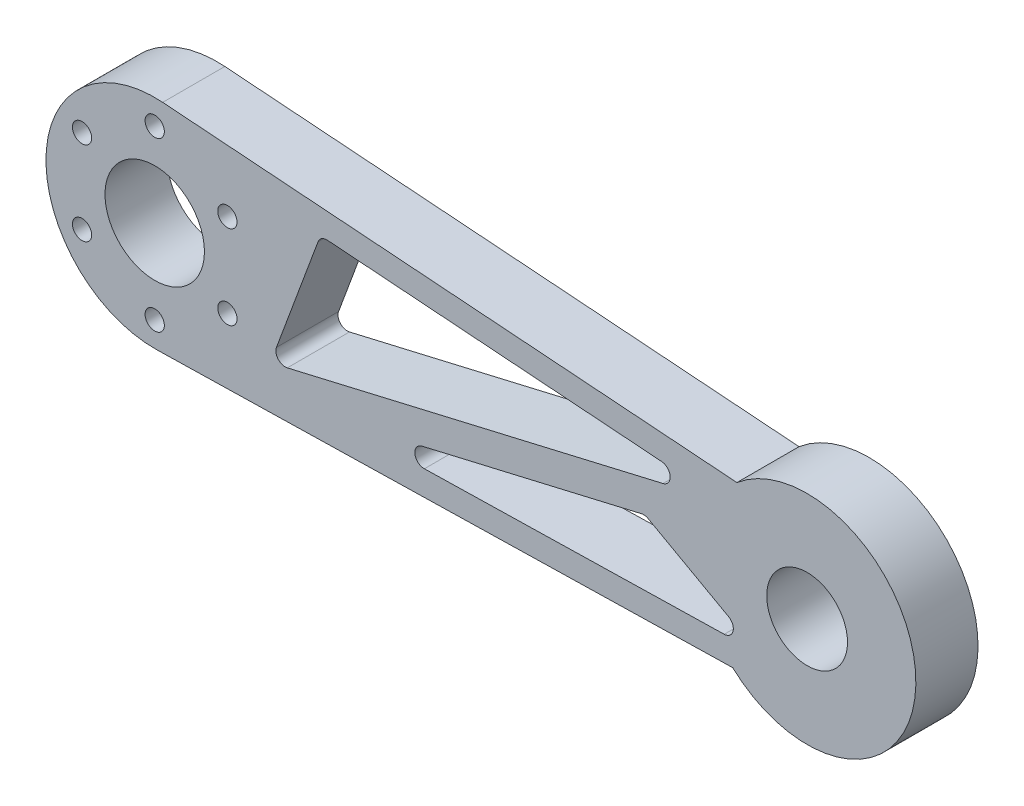
SolidWorks part; units mm, degrees
ref_plane "前视基准面" through (0, 0, 0) normal (0, 0, 1) x (1, 0, 0)
ref_plane "上视基准面" through (0, 0, 0) normal (0, 1, 0) x (1, 0, 0)
ref_plane "右视基准面" through (0, 0, 0) normal (1, 0, 0) x (0, 0, -1)
sketch "草图1" plane through (0, 0, 0) normal (0, 0, 1) x (1, 0, 0)
  line L0 (1.2813, 17.453) -> (105.8807, 9.7742)
  line L1 (0, 0) -> (104.9655, -2.6923) construction
  line L2 (0.3849, -17.4958) -> (105.2404, -15.1893)
  circle A0 centre (0, 0) radius 17.5
  circle A1 centre (104.9655, -2.6923) radius 12.5
  dimension "D1" = 35
  dimension "D2" = 25
  dimension "D3" = 105
extrude "凸台-拉伸1" add sketch "草图1" along normal blind 10
sketch "草图2" plane through (0, 0, 10) normal (0, 0, 1) x (1, 0, 0)
  circle A0 centre (0, 0) radius 13.5 construction
  circle A1 centre (0, 13.5) radius 1.55
  circle A2 centre (11.6913, 6.75) radius 1.55
  circle A3 centre (11.6913, -6.75) radius 1.55
  circle A4 centre (0, -13.5) radius 1.55
  circle A5 centre (-11.6913, -6.75) radius 1.55
  circle A6 centre (-11.6913, 6.75) radius 1.55
  circle A7 centre (0, 0) radius 8
  point P17 (0, 0)
  dimension "D1" = 27
  dimension "D2" = 3.1
  dimension "D4" = 16
  dimension "D3" = 6
extrude "切除-拉伸1" cut sketch "草图2" against normal blind 10
sketch "草图3" plane through (0, 0, 10) normal (0, 0, 1) x (1, 0, 0)
  line L0 (28.9697, -12.866) -> (97.1667, -11.3659)
  line L2 (78.8836, -1.2173) -> (28.9697, -12.866)
  line L3 (0.3849, -17.4958) -> (105.2404, -15.1893) construction
  line L7 (26.6674, 11.5786) -> (18.6174, -10.1476)
  line L8 (18.6174, -10.1476) -> (91.3622, 6.8292)
  line L9 (91.3622, 6.8292) -> (26.6674, 11.5786)
  line L10 (1.2813, 17.453) -> (105.8807, 9.7742) construction
  line L11 (78.8836, -1.2173) -> (97.1667, -11.3659)
  dimension "D1" = 4
  dimension "D2" = 4
  dimension "D3" = 5
extrude "切除-拉伸2" cut sketch "草图3" against normal blind 25
fillet "圆角1" radius 1.5 6 edges at (18.6174, -10.1476, 5) (26.6674, 11.5786, 5) (91.3622, 6.8292, 5) (78.8836, -1.2173, 5) (97.1667, -11.3659, 5) (28.9697, -12.866, 5)
sketch "草图4" plane through (0, 0, 10) normal (0, 0, 1) x (1, 0, 0)
  circle A0 centre (104.9655, -2.6923) radius 6.5
  dimension "D1" = 13
extrude "切除-拉伸3" cut sketch "草图4" against normal blind 25
sketch "草图5" plane through (0, 0, 10) normal (0, 0, 1) x (1, 0, 0)
  line L0 (1.2813, 17.453) -> (105.8807, 9.7742) construction
  line L1 (93.6661, 10.6709) -> (105.8807, 9.7742)
  line L2 (0.3849, -17.4958) -> (105.2404, -15.1893) construction
  line L3 (92.9959, -15.4586) -> (105.2404, -15.1893)
  arc A0 (92.9959, -15.4586) -> (93.6661, 10.6709) centre (104.9655, -2.6923) ccw
  arc A1 (105.2404, -15.1893) -> (105.8807, 9.7742) centre (104.9655, -2.6923) ccw construction
  arc A2 (105.2404, -15.1893) -> (105.8807, 9.7742) centre (104.9655, -2.6923) ccw
  dimension "D1" = 35
extrude "凸台-拉伸2" add sketch "草图5" against normal up to surface (10 mm away) up to face at (111.4655, -2.6923, 0)
